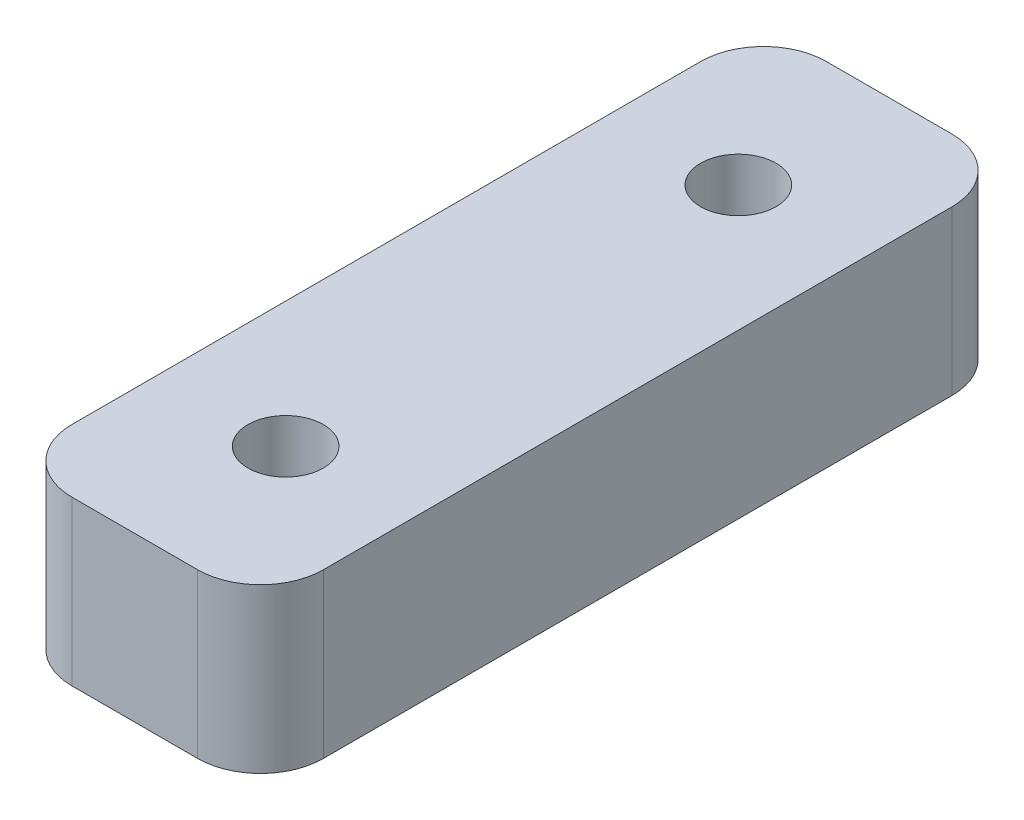
SolidWorks part; units mm, degrees
ref_plane "Front Plane" through (0, 0, 0) normal (0, 0, 1) x (1, 0, 0)
ref_plane "Top Plane" through (0, 0, 0) normal (0, 1, 0) x (1, 0, 0)
ref_plane "Right Plane" through (0, 0, 0) normal (1, 0, 0) x (0, 0, -1)
sketch "Sketch1" plane through (0, 0, 0) normal (0, 1, 0) x (1, 0, 0)
  line L1 (5, 0) -> (15, 0)
  line L2 (0, 5) -> (0, 55)
  line L3 (5, 60) -> (15, 60)
  line L4 (20, 5) -> (20, 55)
  arc A0 (15, 0) -> (20, 5) centre (15, 5) ccw
  arc A1 (0, 55) -> (5, 60) centre (5, 55) cw
  arc A2 (15, 60) -> (20, 55) centre (15, 55) cw
  arc A3 (5, 0) -> (0, 5) centre (5, 5) cw
  point P13 (0, 0)
  dimension "D3" = 5
  dimension "D1" = 20
  dimension "D2" = 60
extrude "Boss-Extrude1" add sketch "Sketch1" along normal blind 13
hole_wizard "Ø6.0mm Dowel Hole1" positions "Sketch2" profile "Sketch3" hole size "Ø6.0" standard "ANSI Metric" end condition through all
sketch "Sketch2" plane through (0, 13, 0) normal (0, 1, 0) x (1, 0, 0)
  line L0 (15, 60) -> (5, 60) construction
  line L1 (0, 55) -> (0, 5) construction
  point P0 (10, 12)
  point P3 (10, 48)
  point P4 (10.3154, 43.0986)
  point P5 (10.2714, 10.6289)
  dimension "D1" = 36
  dimension "D2" = 12
  dimension "D3" = 10
sketch "Sketch3" plane through (10, 13, -12) normal (1, 0, 0) x (0, 0, 1)
  line L0 (0, 0) -> (0, 13)
  line L1 (0, 13) -> (3, 13)
  line L2 (3, 13) -> (3, 0)
  line L5 (3, 0) -> (0, 0)
  line L11 (0, -6.35) -> (0, 107.95) construction
  dimension "Thru Hole Dia." = 6
  dimension "Thru Hole Depth" = 13
